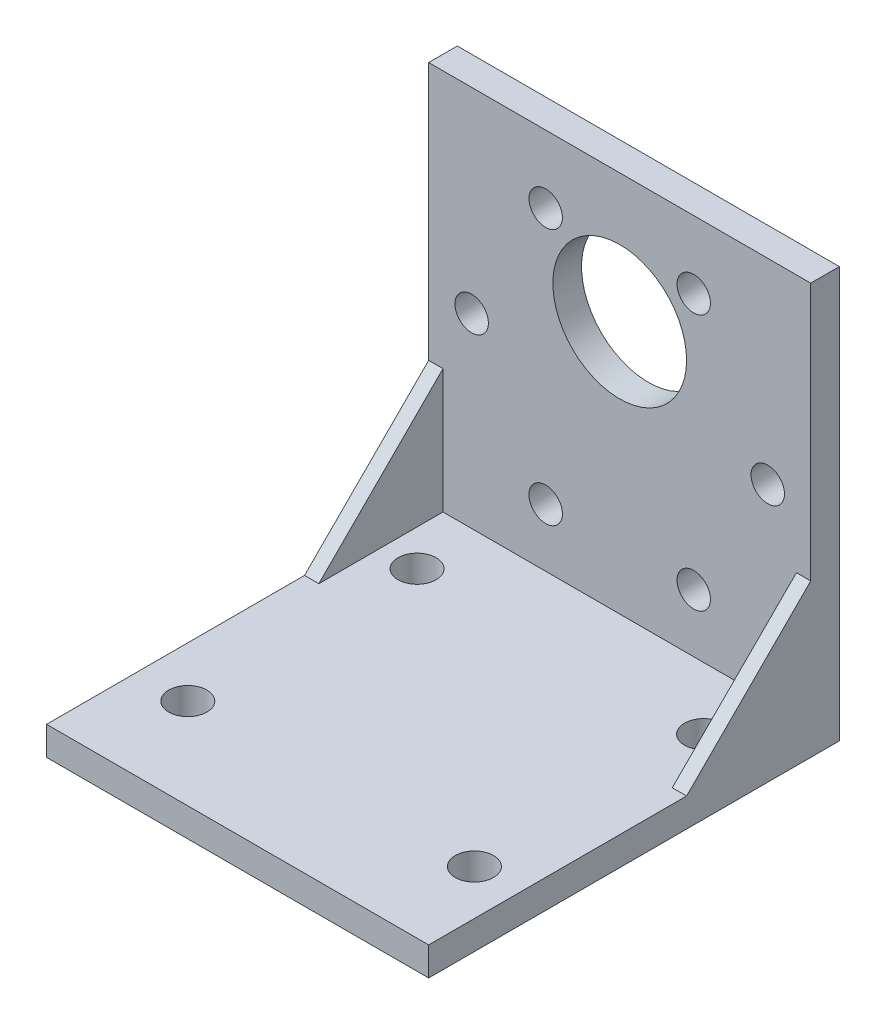
SolidWorks part; units mm, degrees
ref_plane "Front Plane" through (0, 0, 0) normal (0, 0, 1) x (1, 0, 0)
ref_plane "Top Plane" through (0, 0, 0) normal (0, 1, 0) x (1, 0, 0)
ref_plane "Right Plane" through (0, 0, 0) normal (1, 0, 0) x (0, 0, -1)
sketch "Sketch1" plane through (0, 0, 0) normal (0, 1, 0) x (1, 0, 0)
  line L0 (-20, 19.5) -> (20, 19.5)
  line L1 (-20, -21.5) -> (20, -21.5)
  line L2 (-20, -21.5) -> (-20, 21.5)
  line L3 (-20, 21.5) -> (20, 21.5)
  line L4 (20, -21.5) -> (20, 21.5)
  line L5 (-20, -21.5) -> (20, 21.5) construction
  line L6 (-20, 21.5) -> (20, -21.5) construction
  circle A7 centre (-14.7151, 12) radius 2
  circle A8 centre (15.2849, 12) radius 2
  circle A9 centre (-14.7151, -12) radius 2
  circle A10 centre (15.2849, -12) radius 2
  point P0 (0, 0)
  dimension "D4" = 30
  dimension "D5" = 4
  dimension "D6" = 4
  dimension "D7" = 24
  dimension "D8" = 9.5
  dimension "D10" = 4
  dimension "D12" = 4
  dimension "D1" = 2
  dimension "D2" = 40
  dimension "D3" = 43
extrude "Boss-Extrude1" add sketch "Sketch1" against normal blind 3
sketch "Sketch4" plane through (0, 0, 0) normal (0, 1, 0) x (1, 0, 0)
  line L1 (-20, -21.5) -> (-20, 21.5) construction
  line L2 (20, -21.5) -> (20, 21.5) construction
  line L5 (-20, 21.5) -> (20, 21.5)
  line L6 (-20, 21.5) -> (-20, 18.5)
  line L7 (-20, 18.5) -> (20, 18.5)
  line L8 (-20, -21.5) -> (20, -21.5)
  line L9 (20, -21.5) -> (20, 21.5)
  line L10 (20, 21.5) -> (-20, 21.5)
  line L11 (-20, 21.5) -> (-20, -21.5)
  line L12 (-20, -21.5) -> (20, -21.5)
  line L13 (20, -21.5) -> (20, 12.2)
  line L15 (-20, 12.2) -> (-20, -21.5)
  line L16 (20, 21.5) -> (20, 18.5)
  line M13 (20, -21.5) -> (20, 21.5)
  line M14 (20, 21.5) -> (-20, 21.5)
  line M15 (-20, 21.5) -> (-20, -21.5)
  dimension "D1" = 3
  dimension "D2" = 0
extrude "Boss-Extrude2" add sketch "Sketch4" along normal blind 40 contours L7 M15 M13 M14
sketch "Sketch5" plane through (0, 0, -18.5) normal (0, 0, 1) x (1, 0, 0)
  line L0 (-20, 40) -> (20, -1) construction
  line L1 (-20, -1) -> (20, 40) construction
  line L2 (0, 19.5) -> (0, 4) construction
  line L3 (0, 19.5) -> (0, 26.5) construction
  circle A11 centre (0, 26.5) radius 7
  point P18 (0, 19.5)
  point P28 (0, 19.5)
  dimension "D2" = 7
  dimension "D5" = 15.5
  dimension "D6" = 14
extrude "Cut-Extrude5" cut sketch "Sketch5" against normal blind 34
sketch "Sketch8" plane through (0, 0, -18.5) normal (0, 0, 1) x (1, 0, 0)
  line L0 (-20, 40) -> (20, -1) construction
  line L1 (20, 40) -> (-20, -1) construction
  line L2 (0, 19.5) -> (0, 4) construction
  line L3 (-20, 19.5) -> (20, 19.5) construction
  line L4 (-20, 40) -> (-20, 0) construction
  line L5 (20, 40) -> (20, 0) construction
  line L6 (15.5, 19.5) -> (-15.5, 19.5)
  circle A0 centre (0, 4) radius 1.5
  circle A1 centre (-15.5, 19.5) radius 1.75
  circle A3 centre (0, 19.5) radius 15.5
  circle A4 centre (-7.75, 32.9234) radius 1.75
  circle A5 centre (7.75, 32.9234) radius 1.75
  circle A6 centre (15.5, 19.5) radius 1.75
  circle A7 centre (7.75, 6.0766) radius 1.75
  circle A8 centre (-7.75, 6.0766) radius 1.75
  point P21 (0, 19.5)
  point P35 (0, 19.5)
  dimension "D2" = 3
  dimension "D4" = 3.5
  dimension "D5" = 6
  dimension "D1" = 15.5
  dimension "D3" = 31
extrude "Cut-Extrude6" cut sketch "Sketch8" against normal blind 10 contours A7 | A6 | A5 | A4 | A1 | A8
sketch "Sketch9" plane through (20, 0, 0) normal (1, 0, 0) x (0, 0, -1)
  line L0 (18.5, 0) -> (18.5, 13)
  line L1 (18.5, 40) -> (18.5, 0) construction
  line L2 (18.5, 0) -> (5.5, 0)
  line L3 (21.5, 0) -> (-21.5, 0) construction
  line L4 (18.5, 13) -> (5.5, 0)
  dimension "D1" = 13
  dimension "D2" = 13
extrude "Boss-Extrude3" add sketch "Sketch9" against normal blind 1.5
sketch "Sketch10" plane through (-20, 0, 0) normal (-1, 0, 0) x (0, 0, 1)
  line L0 (-18.5, 0) -> (-18.5, 13)
  line L1 (-18.5, 13) -> (-5.5, 0)
  line L2 (-5.5, 0) -> (-18.5, 0)
extrude "Boss-Extrude4" add sketch "Sketch10" against normal blind 1.5
